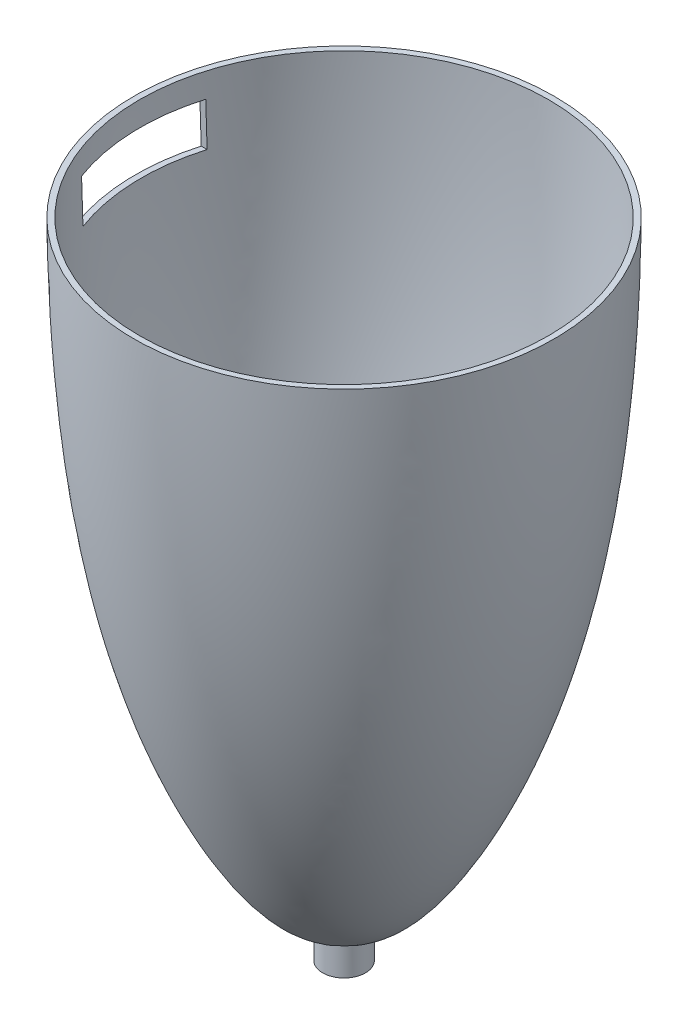
SolidWorks part; units mm, degrees
ref_plane "Front Plane" through (0, 0, 0) normal (0, 0, 1) x (1, 0, 0)
ref_plane "Top Plane" through (0, 0, 0) normal (0, 1, 0) x (1, 0, 0)
ref_plane "Right Plane" through (0, 0, 0) normal (1, 0, 0) x (0, 0, -1)
sketch "Sketch1" plane through (0, 0, 0) normal (0, 1, 0) x (1, 0, 0)
  circle A0 centre (0, 0) radius 4.9985
extrude "Boss-Extrude1" add sketch "Sketch1" along normal blind 10
sketch "Sketch3" plane through (0, 10, 0) normal (0, 1, 0) x (1, 0, 0)
  circle A0 centre (0, 0) radius 3.9975
extrude "Cut-Extrude2" cut sketch "Sketch3" against normal blind 10
sketch "Sketch4" plane through (0, 0, 0) normal (1, 0, 0) x (0, 0, -1)
  line L0 (0, 10) -> (0, 150) construction
  line L1 (3.9975, 10) -> (-3.9975, 10) construction
  line L2 (4.9985, 10) -> (-4.9985, 10) construction
  line L3 (1.6884, 10) -> (0.8924, 10)
  line L4 (49, 150) -> (47.6747, 149.9722)
  spline S0 degree 3 poles (0.8924, 10) (9.4092, 3.3497) (37.7143, 41.3827) (48.5159, 102.6713) (49, 150) knots 0 0 0 0 0.419006 1 1 1 1
  spline S1 degree 3 poles (1.6884, 10) (10.0045, 5.8727) (36.7569, 43.5368) (47.1906, 102.6435) (47.6747, 149.9722) knots 0 0 0 0 0.398399 1 1 1 1
  dimension "D3" = 148.0349
  dimension "D1" = 140
  dimension "D2" = 49
  dimension "D4" = 1.3253
revolve "Revolve4" add sketch "Sketch4" angle 360 about L0
sketch "Sketch5" plane through (0, 0, 0) normal (1, 0, 0) x (0, 0, -1)
  line L1 (-16.5849, 144.3493) -> (13.4151, 144.3493)
  line L2 (-16.5849, 144.3493) -> (-16.5849, 134.3493)
  line L3 (-16.5849, 134.3493) -> (13.4151, 134.3493)
  line L4 (13.4151, 144.3493) -> (13.4151, 134.3493)
  point P4 (13.4151, 144.3493)
  dimension "D1" = 10
  dimension "D2" = 30
extrude "Cut-Extrude3" cut sketch "Sketch5" against normal blind 100
